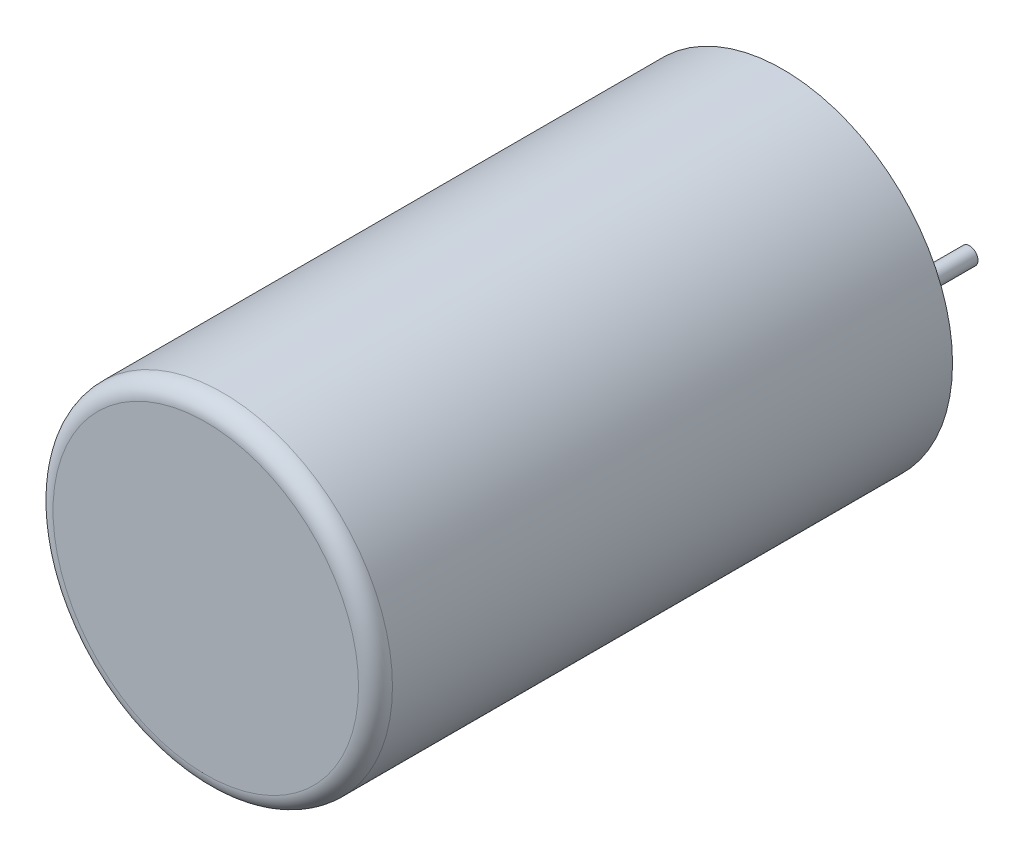
SolidWorks part; units mm, degrees
ref_plane "Спереди" through (0, 0, 0) normal (0, 0, 1) x (1, 0, 0)
ref_plane "Сверху" through (0, 0, 0) normal (0, 1, 0) x (1, 0, 0)
ref_plane "Справа" through (0, 0, 0) normal (1, 0, 0) x (0, 0, -1)
sketch "Эскиз1" plane through (0, 0, 0) normal (0, 0, 1) x (1, 0, 0)
  circle A0 centre (0, 0) radius 5
  dimension "D1" = 10
extrude "Вытянуть1" add sketch "Эскиз1" along normal blind 17
sketch "Эскиз2" plane through (0, 0, 0) normal (0, 0, -1) x (-1, 0, 0)
  line L0 (-8.813, 0) -> (9.6479, 0) construction
  line L1 (0, 0) -> (0, 4.6268) construction
  circle A0 centre (-2.5, 0) radius 0.25
  circle A1 centre (2.5, 0) radius 0.25
  dimension "D1" = 5
  dimension "D2" = 0.5
extrude "Вытянуть2" add sketch "Эскиз2" along normal blind 3
fillet "Скругление1" radius 0.5 1 edges at (5, 0, 17)
